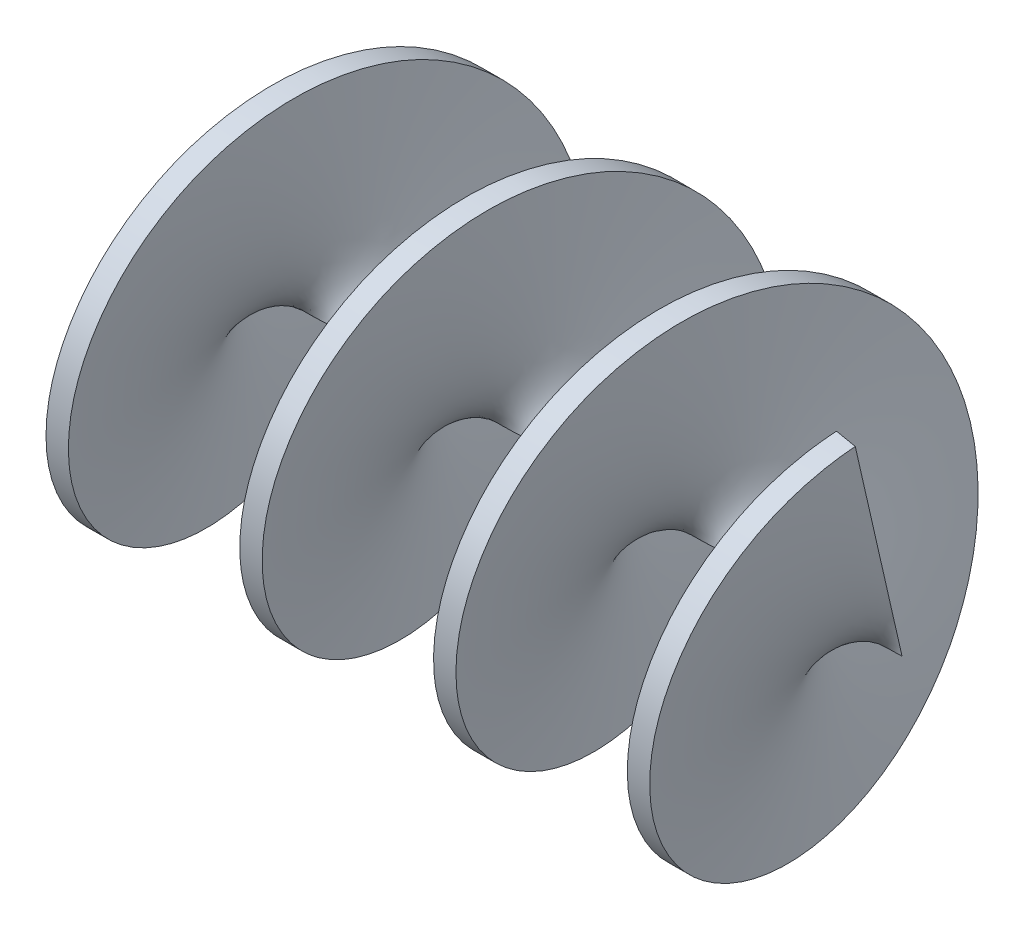
SolidWorks part; units mm, degrees
ref_plane "Front Plane" through (0, 0, 0) normal (0, 0, 1) x (1, 0, 0)
ref_plane "Top Plane" through (0, 0, 0) normal (0, 1, 0) x (1, 0, 0)
ref_plane "Right Plane" through (0, 0, 0) normal (1, 0, 0) x (0, 0, -1)
sketch "Sketch1" plane through (0, 0, 0) normal (1, 0, 0) x (0, 0, -1)
  circle A0 centre (0, 0) radius 7.6
  dimension "D1" = 15.2
curve "Helix/Spiral1" pitch 7 height 26 turns 3.7143
ref_plane "Plane1" through (0, 0, -7.6) normal (0.145, -0.9894, 0) x (-0.9894, -0.145, 0)
sketch "Sketch43" plane through (0, 0, -7.6) normal (0.145, -0.9894, 0) x (-0.9894, -0.145, 0)
  line L0 (0, -7.6) -> (0, 0) construction
  line L1 (0.4, 0) -> (-0.4, 0)
  line L2 (0.4, 0) -> (0.4, -7.6)
  line L3 (0.4, -7.6) -> (-0.4, -7.6)
  line L4 (-0.4, 0) -> (-0.4, -7.6)
  line L5 (0.4, 0) -> (-0.4, -7.6) construction
  line L6 (0.4, -7.6) -> (-0.4, 0) construction
  point P0 (0, -3.8)
  point P7 (0, 0)
  dimension "D1" = 0.8
  dimension "D2" = 7.6
sweep "Sweep7" add profiles "Sketch43" path "Helix/Spiral1"
